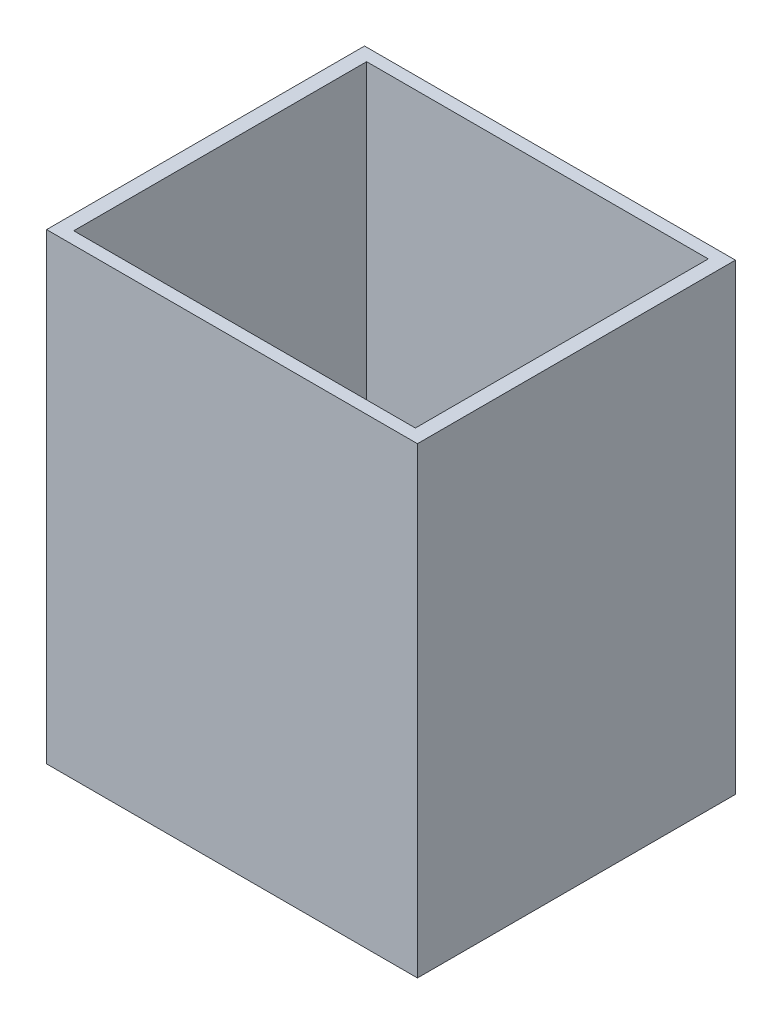
SolidWorks part; units mm, degrees
ref_plane "Front Plane" through (0, 0, 0) normal (0, 0, 1) x (1, 0, 0)
ref_plane "Top Plane" through (0, 0, 0) normal (0, 1, 0) x (1, 0, 0)
ref_plane "Right Plane" through (0, 0, 0) normal (1, 0, 0) x (0, 0, -1)
sketch "Sketch1" plane through (0, 0, 0) normal (0, 1, 0) x (1, 0, 0)
  line L1 (-38.07, 32.64) -> (38.07, 32.64)
  line L2 (-38.07, 32.64) -> (-38.07, -32.64)
  line L3 (-38.07, -32.64) -> (38.07, -32.64)
  line L4 (38.07, 32.64) -> (38.07, -32.64)
  line L5 (-38.07, 32.64) -> (38.07, -32.64) construction
  line L6 (-38.07, -32.64) -> (38.07, 32.64) construction
  point P0 (0, 0)
  dimension "D1" = 76.14
  dimension "D2" = 65.28
extrude "Boss-Extrude1" add sketch "Sketch1" along normal blind 80
sketch "Sketch3" plane through (0, 0, 0) normal (0, -1, 0) x (1, 0, 0)
  line L1 (38.07, -32.64) -> (-38.07, -32.64)
  line L2 (38.07, -32.64) -> (38.07, 32.64)
  line L3 (38.07, 32.64) -> (-38.07, 32.64)
  line L4 (-38.07, -32.64) -> (-38.07, 32.64)
  line L5 (38.07, -32.64) -> (-38.07, 32.64) construction
  line L6 (38.07, 32.64) -> (-38.07, -32.64) construction
  line L7 (34.93, -29.9479) -> (-34.93, -29.9479)
  line L8 (34.93, -29.9479) -> (34.93, 29.9479)
  line L9 (34.93, 29.9479) -> (-34.93, 29.9479)
  line L10 (-34.93, -29.9479) -> (-34.93, 29.9479)
  line L11 (34.93, -29.9479) -> (-34.93, 29.9479) construction
  line L12 (34.93, 29.9479) -> (-34.93, -29.9479) construction
  point P0 (0, 0)
  point P7 (0, 0)
  dimension "D1" = 3.14
extrude "Boss-Extrude2" add sketch "Sketch3" along normal blind 15
sketch "Sketch4" plane through (0, 80, 0) normal (0, 1, 0) x (1, 0, 0)
  line L1 (38.07, -32.64) -> (-38.07, -32.64) construction
  line L2 (38.07, -32.64) -> (38.07, 32.64) construction
  line L3 (38.07, 32.64) -> (-38.07, 32.64) construction
  line L4 (-38.07, -32.64) -> (-38.07, 32.64) construction
  line L5 (38.07, -32.64) -> (-38.07, 32.64) construction
  line L6 (38.07, 32.64) -> (-38.07, -32.64) construction
  line L7 (35.07, -30.0679) -> (-35.07, -30.0679)
  line L8 (35.07, -30.0679) -> (35.07, 30.0679)
  line L9 (35.07, 30.0679) -> (-35.07, 30.0679)
  line L10 (-35.07, -30.0679) -> (-35.07, 30.0679)
  line L11 (35.07, -30.0679) -> (-35.07, 30.0679) construction
  line L12 (35.07, 30.0679) -> (-35.07, -30.0679) construction
  point P0 (0, 0)
  point P7 (0, 0)
  dimension "D1" = 3
extrude "Cut-Extrude1" cut sketch "Sketch4" against normal blind 75
sketch "Sketch5" plane through (0, 0, 0) normal (0, -1, 0) x (1, 0, 0)
  line L1 (34.93, -29.9479) -> (-34.93, -29.9479) construction
  line L2 (34.93, -29.9479) -> (34.93, 29.9479) construction
  line L3 (34.93, 29.9479) -> (-34.93, 29.9479) construction
  line L4 (-34.93, -29.9479) -> (-34.93, 29.9479) construction
  line L5 (34.93, -29.9479) -> (-34.93, 29.9479) construction
  line L6 (34.93, 29.9479) -> (-34.93, -29.9479) construction
  line L7 (31.79, -27.2557) -> (-31.79, -27.2557)
  line L8 (31.79, -27.2557) -> (31.79, 27.2557)
  line L9 (31.79, 27.2557) -> (-31.79, 27.2557)
  line L10 (-31.79, -27.2557) -> (-31.79, 27.2557)
  line L11 (31.79, -27.2557) -> (-31.79, 27.2557) construction
  line L12 (31.79, 27.2557) -> (-31.79, -27.2557) construction
  point P0 (0, 0)
  point P7 (0, 0)
  dimension "D1" = 3.14
extrude "Boss-Extrude3" add sketch "Sketch5" along normal blind 15
